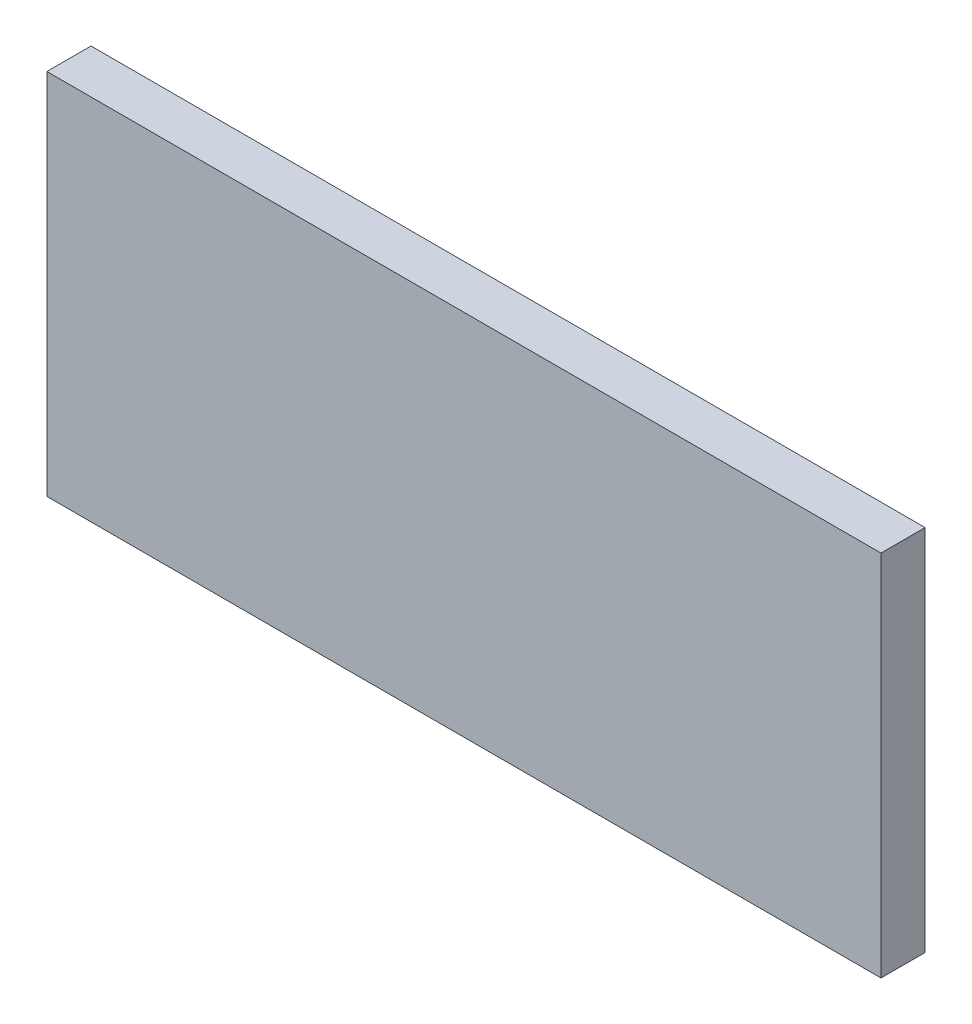
SolidWorks part; units mm, degrees
ref_plane "Front Plane" through (0, 0, 0) normal (0, 0, 1) x (1, 0, 0)
ref_plane "Top Plane" through (0, 0, 0) normal (0, 1, 0) x (1, 0, 0)
ref_plane "Right Plane" through (0, 0, 0) normal (1, 0, 0) x (0, 0, -1)
sketch "Sketch1" plane through (0, 0, 0) normal (0, 0, 1) x (1, 0, 0)
  line L1 (0, 0) -> (340, 0)
  line L2 (0, 0) -> (0, 150)
  line L3 (0, 150) -> (340, 150)
  line L4 (340, 0) -> (340, 150)
  dimension "D1" = 340
  dimension "D2" = 150
extrude "Boss-Extrude1" add sketch "Sketch1" along normal blind 18
